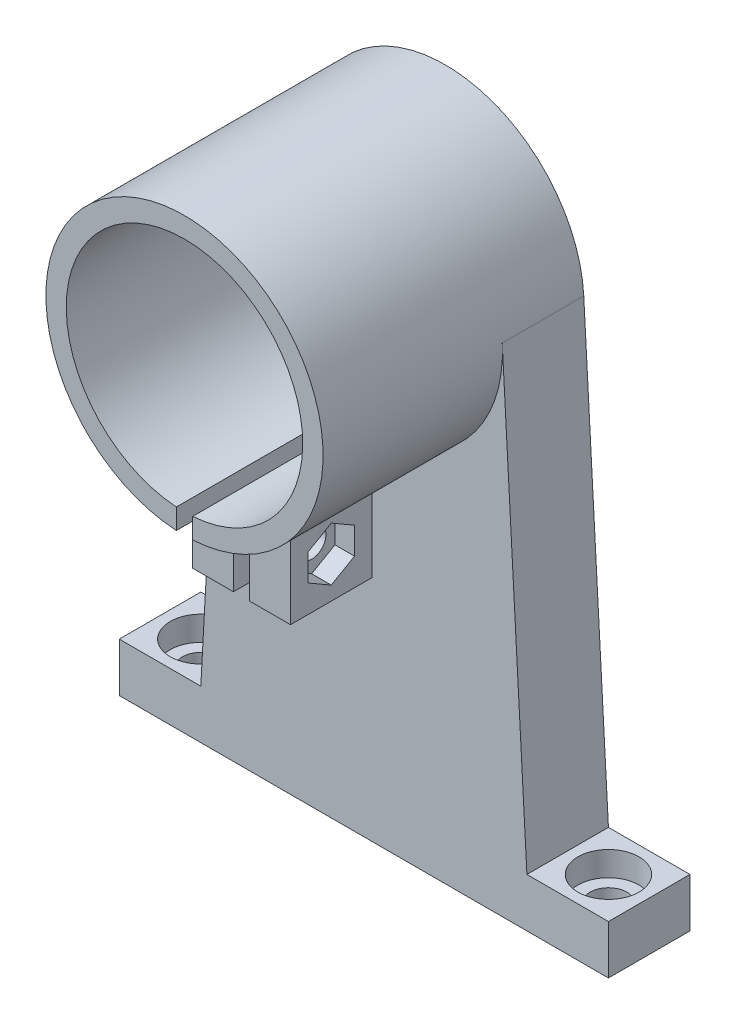
SolidWorks part; units mm, degrees
material "PET"
ref_plane "Piano frontale" through (0, 0, 0) normal (0, 0, 1) x (1, 0, 0)
ref_plane "Piano superiore" through (0, 0, 0) normal (0, 1, 0) x (1, 0, 0)
ref_plane "Piano destro" through (0, 0, 0) normal (1, 0, 0) x (0, 0, -1)
sketch "Schizzo1" plane through (0, 0, 0) normal (0, 0, 1) x (1, 0, 0)
  circle A0 centre (0, 0) radius 17
  circle A1 centre (0, 0) radius 5.1
  dimension "D1" = 34
  dimension "D2" = 10.2
extrude "Estrusione-Estrusione1" add sketch "Schizzo1" along normal blind 2
sketch "Schizzo2" plane through (0, 0, 2) normal (0, 0, 1) x (1, 0, 0)
  circle A0 centre (0, 0) radius 14.5
  circle A1 centre (0, 0) radius 17
  circle A2 centre (0, 0) radius 17
  dimension "D2" = 29
  dimension "D1" = 0
extrude "Estrusione-Estrusione2" add sketch "Schizzo2" along normal blind 30
sketch "Schizzo3" plane through (0, 0, 32) normal (0, 0, 1) x (1, 0, 0)
  line L0 (0, 0) -> (0, -17)
  line L2 (-1, -13.5) -> (1, -13.5)
  line L3 (-1, -13.5) -> (-1, -20.5)
  line L4 (-1, -20.5) -> (1, -20.5)
  line L5 (1, -13.5) -> (1, -20.5)
  line L6 (-1, -13.5) -> (1, -20.5) construction
  line L7 (-1, -20.5) -> (1, -13.5) construction
  circle A0 centre (0, 0) radius 17 construction
  circle M3 centre (0, 0) radius 17
  circle M4 centre (0, 0) radius 14.5
  dimension "D1" = 2
  dimension "D2" = 7
extrude "Taglio-Estrusione1" cut sketch "Schizzo3" against normal blind 24 contours L3 L0 M4 M3 | L5 L0 M4 M3
sketch "Schizzo4" plane through (1, 0, 0) normal (-1, 0, 0) x (0, 0, 1)
  line L0 (8, -16.9706) -> (32, -16.9706) construction
  line L1 (15, -26.9706) -> (25, -26.9706)
  line L2 (15, -26.9706) -> (15, -16.9706)
  line L3 (15, -16.9706) -> (25, -16.9706)
  line L4 (25, -26.9706) -> (25, -16.9706)
  line L5 (25, -26.9706) -> (15, -16.9706) construction
  circle A0 centre (20, -21.9706) radius 1.75
  point P4 (20, -16.9706)
  dimension "D2" = 3.5
  dimension "D1" = 10
extrude "Estrusione-Estrusione4" add sketch "Schizzo4" against normal blind 5
sketch "Schizzo6" plane through (0, -16.9706, 0) normal (0, 1, 0) x (1, 0, 0)
  line L4 (1, -15) -> (1, -25)
  line L5 (1, -25) -> (6, -25)
  line L6 (6, -25) -> (6, -15)
  line L7 (6, -15) -> (1, -15)
  line L8 (1, -15) -> (1, -25)
  line L9 (1, -25) -> (6, -25)
  line L10 (6, -25) -> (6, -15)
  line L11 (6, -15) -> (1, -15)
  dimension "D1" = 0
extrude "Estrusione-Estrusione5" add sketch "Schizzo6" along normal blind 1
ref_plane "Piano2" through (0, 0, 0) normal (1, 0, 0) x (0, 0, -1)
mirror "Specchia4" about plane through (0, 0, 0) normal (1, 0, 0) of "Estrusione-Estrusione5", "Estrusione-Estrusione4"
mirror "Specchia5" about plane through (0, 0, 0) normal (1, 0, 0) of "Estrusione-Estrusione4"
sketch "Schizzo7" plane through (6, 0, 0) normal (1, 0, 0) x (0, 0, -1)
  line L0 (-15, -15.9706) -> (-15, -26.9706) construction
  line L1 (-20, -18.6797) -> (-22.85, -20.3251)
  line L2 (-22.85, -20.3251) -> (-22.85, -23.616)
  line L3 (-22.85, -23.616) -> (-20, -25.2615)
  line L4 (-20, -25.2615) -> (-17.15, -23.616)
  line L5 (-17.15, -23.616) -> (-17.15, -20.3251)
  line L6 (-17.15, -20.3251) -> (-20, -18.6797)
  circle A0 centre (-20, -21.9706) radius 2.85 construction
  dimension "D1" = 5.7
extrude "Taglio-Estrusione2" cut sketch "Schizzo7" against normal blind 2.4
sketch "Schizzo8" plane through (-6, 0, 0) normal (-1, 0, 0) x (0, 0, 1)
  circle A0 centre (20, -21.9706) radius 3.5
  dimension "D1" = 7
extrude "Taglio-Estrusione3" cut sketch "Schizzo8" against normal blind 2.4
sketch "Schizzo9" plane through (0, 0, 0) normal (0, 0, -1) x (-1, 0, 0)
  line L0 (-30, -60) -> (30, -60)
  line L1 (-30, -60) -> (-30, -54)
  line L2 (-30, -54) -> (-20, -54)
  line L3 (30, -60) -> (30, -54)
  line L4 (-20, -54) -> (-16.9743, 0.9349)
  line L5 (30, -54) -> (20, -54)
  line L6 (20, -54) -> (16.9743, 0.9349)
  arc A1 (-16.9743, 0.9349) -> (16.9743, 0.9349) centre (0, 0) ccw
  circle A2 centre (0, 0) radius 17 construction
  point P2 (0, -60)
  dimension "D1" = 60
  dimension "D2" = 6
  dimension "D3" = 10
  dimension "D4" = 60
extrude "Estrusione-Estrusione6" add sketch "Schizzo9" against normal blind 10
sketch "Schizzo10" plane through (0, -54, 0) normal (0, 1, 0) x (1, 0, 0)
  line L0 (20, -10) -> (30, 0) construction
  line L1 (-20, 0) -> (-30, -10) construction
  circle A0 centre (25, -5) radius 2.25
  circle A1 centre (-25, -5) radius 2.25
  dimension "D1" = 4.5
extrude "Taglio-Estrusione4" cut sketch "Schizzo10" against normal blind 6
sketch "Schizzo11" plane through (0, -54, 0) normal (0, 1, 0) x (1, 0, 0)
  circle A0 centre (-25, -5) radius 3.75
  circle A1 centre (25, -5) radius 3.75
  dimension "D1" = 7.5
extrude "Taglio-Estrusione5" cut sketch "Schizzo11" against normal blind 3
